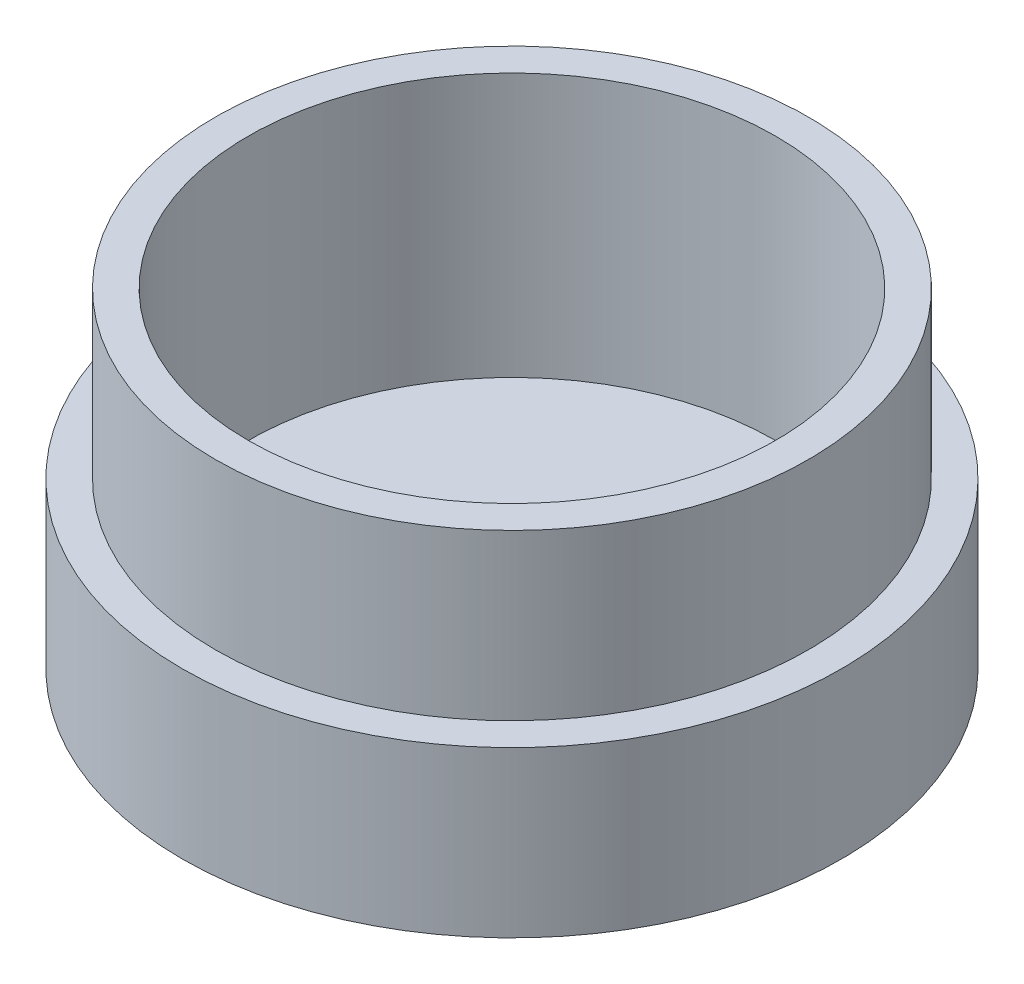
SolidWorks part; units mm, degrees
ref_plane "Front Plane" through (0, 0, 0) normal (0, 0, 1) x (1, 0, 0)
ref_plane "Top Plane" through (0, 0, 0) normal (0, 1, 0) x (1, 0, 0)
ref_plane "Right Plane" through (0, 0, 0) normal (1, 0, 0) x (0, 0, -1)
sketch "Sketch1" plane through (0, 0, 0) normal (0, 1, 0) x (1, 0, 0)
  circle A0 centre (0, 0) radius 25.4
extrude "Boss-Extrude1" add sketch "Sketch1" along normal blind 25.4
shell "Shell2" thickness 5.08
sketch "Sketch3" plane through (0, 25.4, 0) normal (0, 1, 0) x (1, 0, 0)
  circle A0 centre (0, 0) radius 22.86
  circle A1 centre (0, 0) radius 25.4
extrude "Cut-Extrude3" cut sketch "Sketch3" against normal blind 12.7 contours A0 | A1
